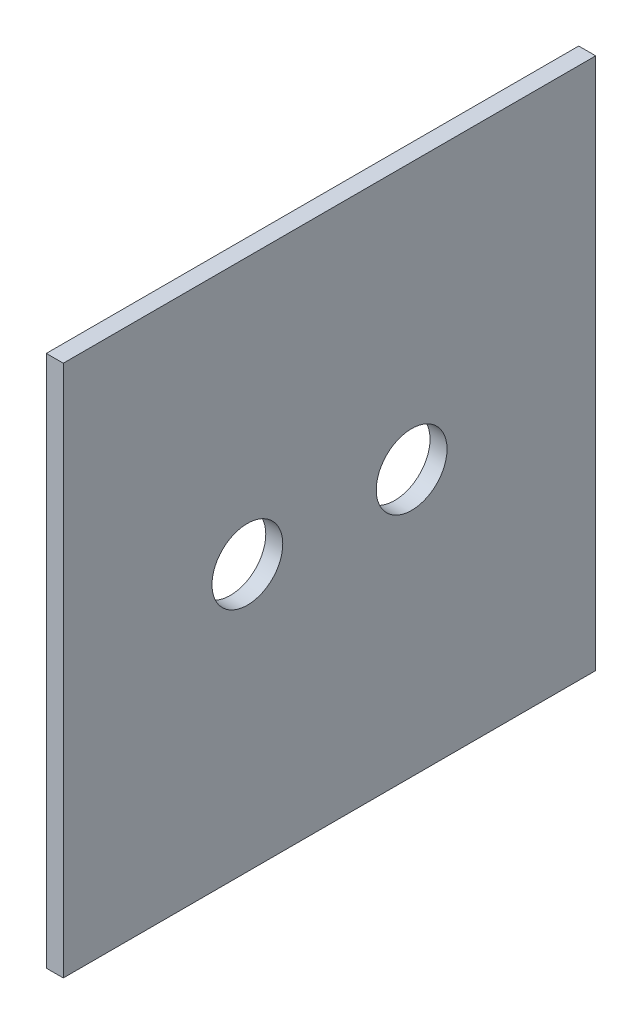
SolidWorks part; units mm, degrees
ref_plane "Front Plane" through (0, 0, 0) normal (0, 0, 1) x (1, 0, 0)
ref_plane "Top Plane" through (0, 0, 0) normal (0, 1, 0) x (1, 0, 0)
ref_plane "Right Plane" through (0, 0, 0) normal (1, 0, 0) x (0, 0, -1)
sketch "Sketch1" plane through (0, 0, 0) normal (1, 0, 0) x (0, 0, -1)
  line L1 (-80.7174, 121.4592) -> (107.2826, 121.4592)
  line L2 (-80.7174, 121.4592) -> (-80.7174, -66.5408)
  line L3 (-80.7174, -66.5408) -> (107.2826, -66.5408)
  line L4 (107.2826, 121.4592) -> (107.2826, -66.5408)
  circle A0 centre (42.2826, 27.4592) radius 12.5
  circle A1 centre (-15.7174, 27.4592) radius 12.5
  dimension "D1" = 188
  dimension "D2" = 188
  dimension "D3" = 94
  dimension "D4" = 94
  dimension "D5" = 65
  dimension "D6" = 65
extrude "Boss-Extrude1" add sketch "Sketch1" along normal blind 6
